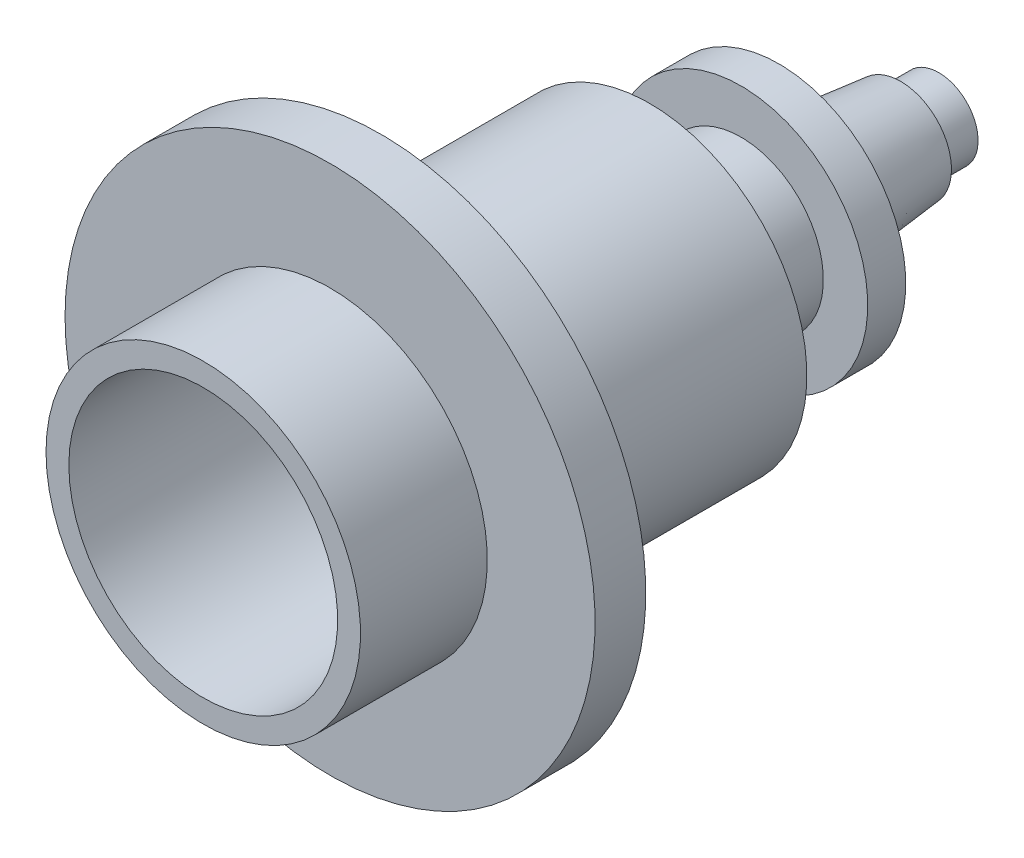
SolidWorks part; units mm, degrees
ref_plane "Top" through (0, 0, 0) normal (0, 0, 1) x (1, 0, 0)
ref_plane "Front" through (0, 0, 0) normal (0, 1, 0) x (1, 0, 0)
ref_plane "Right" through (0, 0, 0) normal (1, 0, 0) x (0, 0, -1)
sketch "Body Sketch" plane through (0, 0, 0) normal (0, 1, 0) x (1, 0, 0)
  line L0 (0, 0) -> (0, -14.5) construction
  line L2 (2.65, -14.5) -> (3.1, -14.5)
  line L3 (3.1, -14.5) -> (3.1, -12)
  line L4 (3.1, -12) -> (5.225, -12)
  line L5 (5.225, -12) -> (5.225, -11)
  line L6 (5.225, -11) -> (3.1, -11)
  line L7 (3.1, -11) -> (3.1, -5.7)
  line L8 (3.1, -5.7) -> (1.625, -5.3)
  line L9 (1.625, -5.3) -> (1.625, -3.9)
  line L10 (1.625, -3.9) -> (2.5, -3.9)
  line L11 (2.5, -3.9) -> (2.5, -3.15)
  line L12 (2.5, -3.15) -> (1.25, -3.15)
  line L13 (1.25, -3.15) -> (1, -0.75)
  line L14 (1, -0.75) -> (0.775, -0.75)
  line L15 (0.775, -0.75) -> (0.775, 0)
  line L16 (0.775, 0) -> (0.25, 0)
  line L17 (0.25, 0) -> (0.25, -5.7042)
  line L18 (0.25, -5.7042) -> (2.65, -6.3551)
  line L19 (2.65, -6.3551) -> (2.65, -14.5)
  point P19 (0.5125, 0)
  dimension "D1" = 0.25
  dimension "D2" = 0.775
  dimension "D3" = 2.5
  dimension "D4" = 0.75
  dimension "D5" = 14.5
  dimension "D6" = 1.25
  dimension "D7" = 1
  dimension "D8" = 0.75
  dimension "D9" = 2.4
  dimension "D10" = 1.625
  dimension "D11" = 1.4
  dimension "D12" = 0.4
  dimension "D13" = 3.1
  dimension "D14" = 5.225
  dimension "D15" = 1
  dimension "D16" = 2.5
  dimension "D17" = 2.65
  dimension "D18" = 0.75
revolve "Body Revolve" add sketch "Body Sketch" angle 360 about L0
equation "\"D10@Body Sketch\"=3.25/2"
